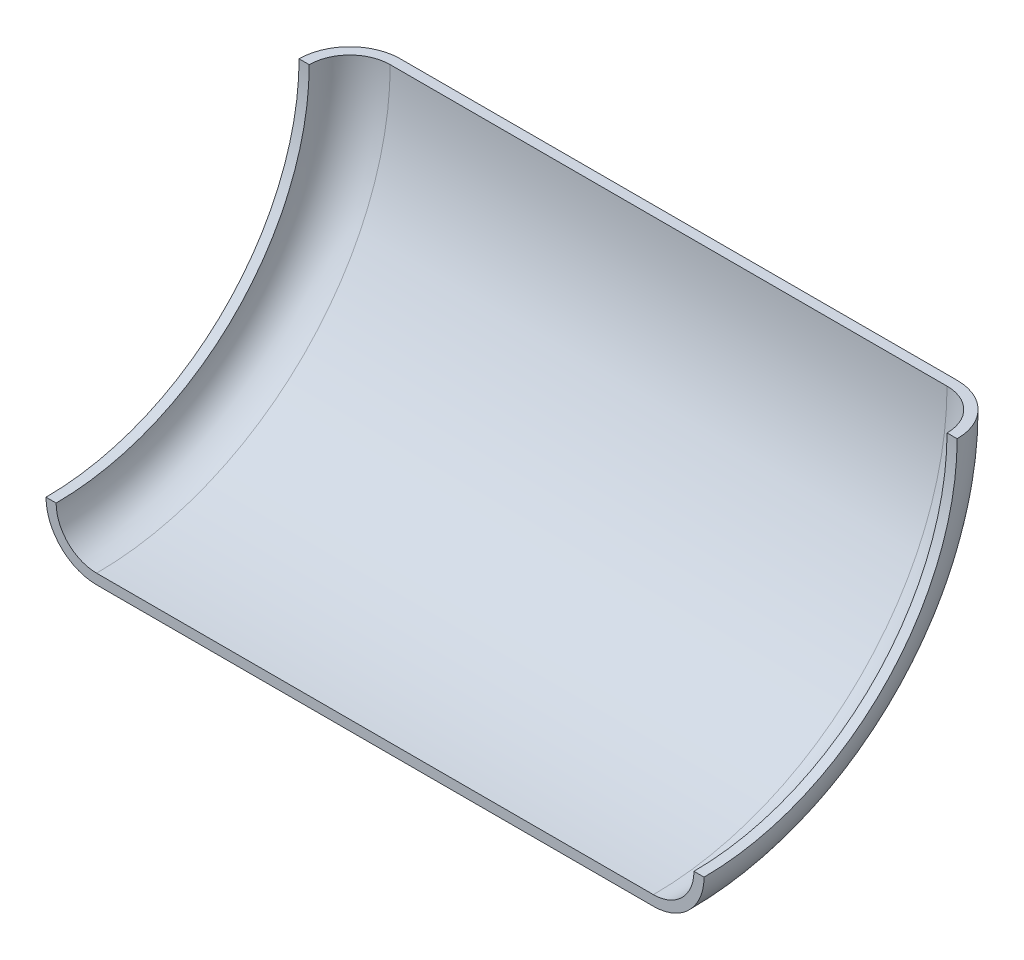
SolidWorks part; units mm, degrees
ref_plane "Front Plane" through (0, 0, 0) normal (0, 0, 1) x (1, 0, 0)
ref_plane "Top Plane" through (0, 0, 0) normal (0, 1, 0) x (1, 0, 0)
ref_plane "Right Plane" through (0, 0, 0) normal (1, 0, 0) x (0, 0, -1)
sketch "Sketch1" plane through (0, 0, 0) normal (0, 0, 1) x (1, 0, 0)
  line L0 (-69.85, 0) -> (69.85, 0)
  line L1 (69.85, 0) -> (82.55, 0) construction
  line L2 (82.55, 0) -> (82.55, 12.7) construction
  line L3 (0, 19.8378) -> (0, -30.07) construction
  line L4 (0, 0) -> (0, 2.54)
  line L5 (-69.85, 2.54) -> (69.85, 2.54)
  line L6 (82.55, 12.7) -> (80.01, 12.7)
  line L7 (-82.55, 12.7) -> (-80.01, 12.7)
  arc A0 (69.85, 0) -> (82.55, 12.7) centre (69.85, 12.7) ccw
  arc A1 (-69.85, 0) -> (-82.55, 12.7) centre (-69.85, 12.7) cw
  arc A2 (69.85, 2.54) -> (80.01, 12.7) centre (69.85, 12.7) ccw
  arc A3 (-69.85, 2.54) -> (-80.01, 12.7) centre (-69.85, 12.7) cw
  point P11 (0, 0)
  dimension "D1" = 69.85
  dimension "D2" = 12.7
  dimension "D3" = 12.7
  dimension "D4" = 2.54
sketch "Sketch2" plane through (0, 0, 0) normal (1, 0, 0) x (0, 0, -1)
  line L0 (0, 0) -> (76.2, 0) construction
  line L1 (76.2, 0) -> (76.2, 76.2) construction
  arc A0 (0, 0) -> (76.2, 76.2) centre (0, 76.2) ccw
  dimension "D1" = 76.2
  dimension "D2" = 76.2
sweep "Sweep1" add profiles "Sketch1" path "Sketch2"
